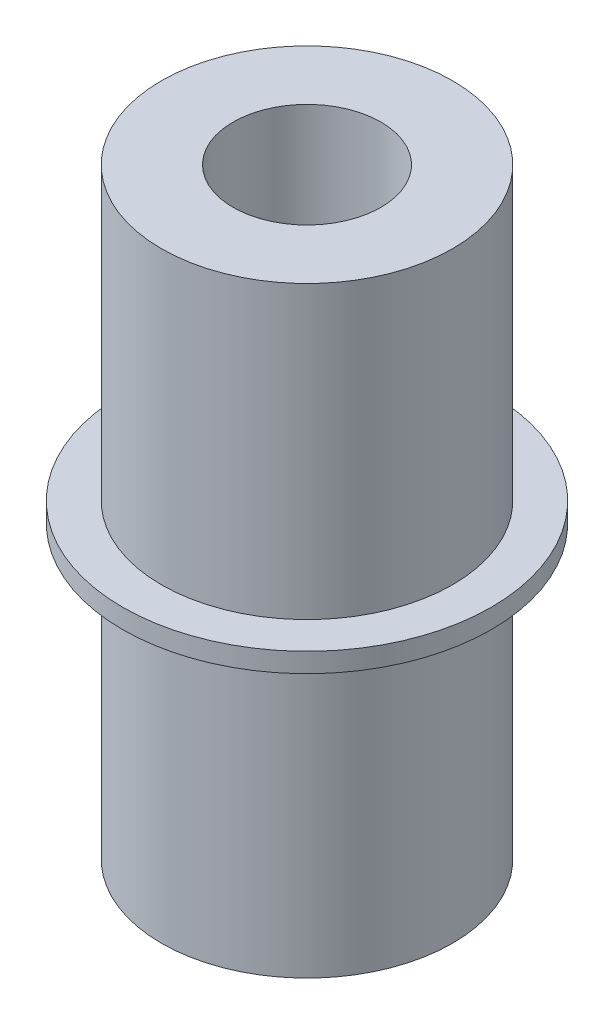
SolidWorks part; units mm, degrees
ref_plane "Front Plane" through (0, 0, 0) normal (0, 0, 1) x (1, 0, 0)
ref_plane "Top Plane" through (0, 0, 0) normal (0, 1, 0) x (1, 0, 0)
ref_plane "Right Plane" through (0, 0, 0) normal (1, 0, 0) x (0, 0, -1)
sketch "Sketch1" plane through (0, 0, 0) normal (0, 0, 1) x (1, 0, 0)
  line L0 (-3.81, -15.5) -> (-3.81, 15.5)
  line L13 (-3.81, 15.5) -> (-7.5, 15.5)
  line L14 (-7.5, 15.5) -> (-7.5, 0.5)
  line L15 (-7.5, 0.5) -> (-9.5, 0.5)
  line L16 (-9.5, 0.5) -> (-9.5, -0.5)
  line L17 (-9.5, -0.5) -> (-7.5, -0.5)
  line L18 (-7.5, -0.5) -> (-7.5, -15.5)
  line L19 (-7.5, -15.5) -> (-3.81, -15.5)
  line L20 (0, 0) -> (0, 9.5041) construction
  point P10 (-3.81, 0)
  point P11 (0, 0)
  point P13 (-6.5972, -0.5)
  dimension "D1" = 3.81
  dimension "D2" = 7.5
  dimension "D3" = 1
  dimension "D4" = 15
  dimension "D5" = 2
revolve "Revolve1" add sketch "Sketch1" angle 360 about L20
